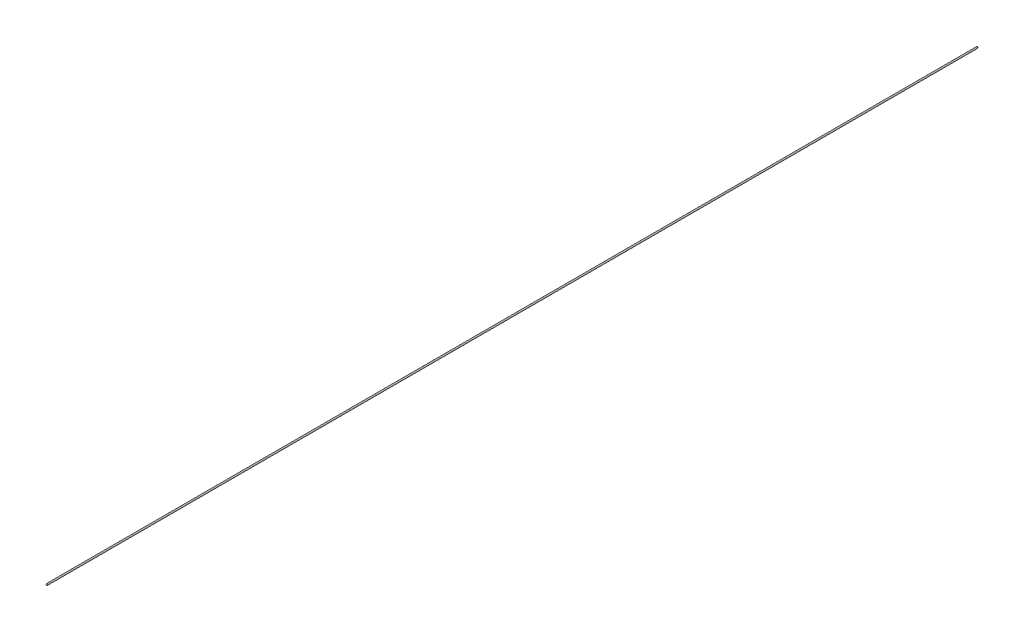
SolidWorks part; units mm, degrees
material "自定义塑料"
ref_plane "前视基准面" through (0, 0, 0) normal (0, 0, 1) x (1, 0, 0)
ref_plane "上视基准面" through (0, 0, 0) normal (0, 1, 0) x (1, 0, 0)
ref_plane "右视基准面" through (0, 0, 0) normal (1, 0, 0) x (0, 0, -1)
sketch "草图2" plane through (0, 0, 0) normal (0, 0, 1) x (1, 0, 0)
  circle A0 centre (0, 0) radius 25
  dimension "D1" = 50
extrude "凸台-拉伸1" add sketch "草图2" along normal blind 31100
sketch "草图7" plane through (0, 0, 0) normal (1, 0, 0) x (0, 0, -1)
  line L1 (-21000, 0) -> (29000, 0) construction
  line L2 (-31100, 25) -> (-31100, -25) construction
  line L3 (-31100, -1000) -> (-31100, 49000) construction
  line L4 (-20995.8735, 25) -> (29004.1265, 25) construction
  line L5 (0, 25) -> (-31100, 25) construction
  line L6 (-31100, 25) -> (-31100, 0)
  line L7 (-31100, 0) -> (-31125, 0)
  arc A0 (-31100, 25) -> (-31125, 0) centre (-31100, 0) ccw
  point P7 (-31100, 0)
revolve "旋转2" add sketch "草图7" angle 360 about L1
sketch "草图8" plane through (0, 0, 0) normal (1, 0, 0) x (0, 0, -1)
  line L0 (25, 0) -> (0, 0)
  line L1 (0, 0) -> (0, 25)
  arc A0 (0, 25) -> (25, 0) centre (0, 0) cw
revolve "旋转3" add sketch "草图8" angle 360 about L0
